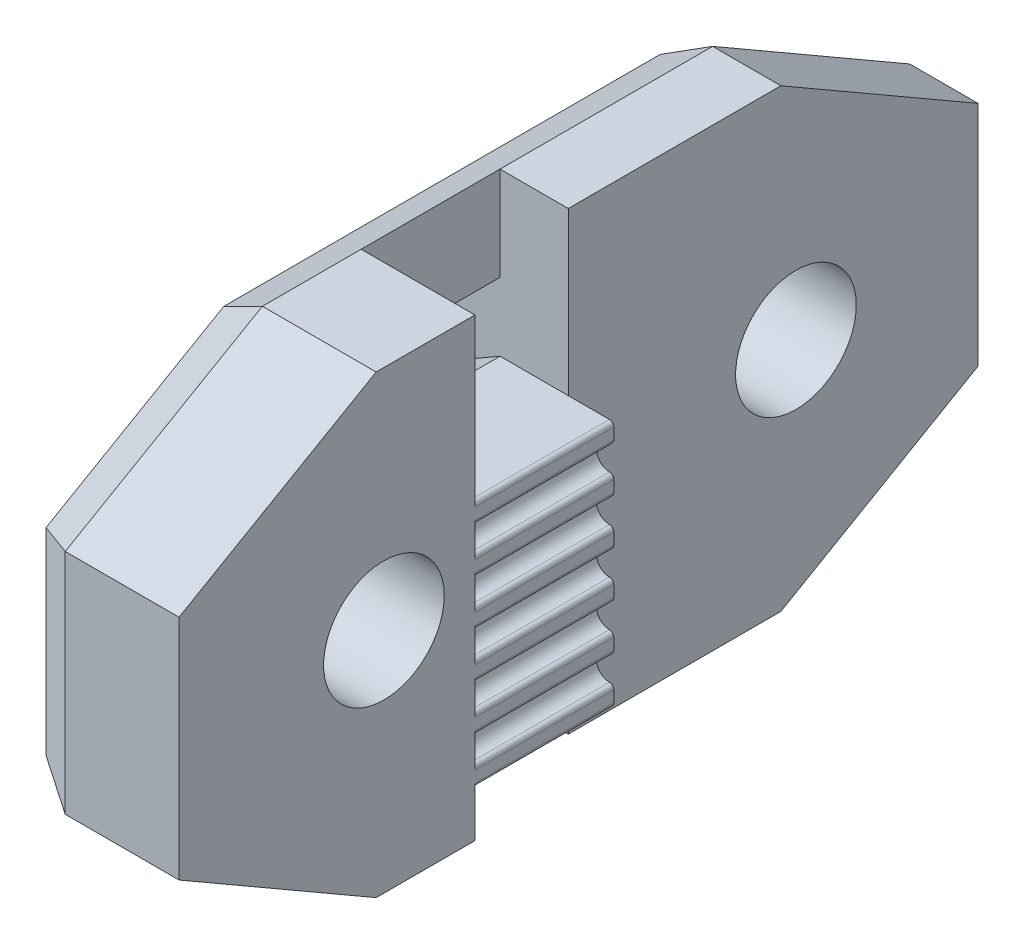
SolidWorks part; units mm, degrees
material "ABS"
ref_plane "Ebene vorne" through (0, 0, 0) normal (0, 0, 1) x (1, 0, 0)
ref_plane "Ebene oben" through (0, 0, 0) normal (0, 1, 0) x (1, 0, 0)
ref_plane "Ebene rechts" through (0, 0, 0) normal (1, 0, 0) x (0, 0, -1)
sketch "Skizze1" plane through (0, 0, 0) normal (0, 0, 1) x (1, 0, 0)
  line L0 (0, 0) -> (0, 9.44)
  line L1 (0, 9.44) -> (-7.24, 9.44) construction
  line L2 (-7.05, 10.19) -> (-7.05, 10.69)
  line L3 (-7.05, 8.69) -> (-7.05, 8.19)
  line L4 (-7.24, 10.88) -> (-9.24, 10.88)
  line L5 (-9.24, 10.88) -> (-9.24, 0)
  line L6 (-7.05, 6.69) -> (-7.05, 6.19)
  line L7 (-7.05, 4.69) -> (-7.05, 4.19)
  line L8 (-7.05, 2.69) -> (-7.05, 2.19)
  line L9 (-7.05, 0.69) -> (-7.05, 0.19)
  line L10 (-7.05, -1.31) -> (-7.05, -1.81) construction
  line L11 (-7.05, -3.31) -> (-7.05, -3.81) construction
  line L12 (-7.05, -5.31) -> (-7.05, -5.81) construction
  line L13 (-7.05, -7.31) -> (-7.05, -7.81) construction
  line L14 (-7.05, -9.31) -> (-7.05, -9.81) construction
  line L15 (-7.24, 0) -> (-9.24, 0)
  line L16 (0, 9.44) -> (0, 10.88)
  line L17 (0, 10.88) -> (-6, 10.88)
  line L18 (-6, 10.88) -> (-6, 0)
  line L19 (-6, 0) -> (0, 0)
  arc A0 (-7.24, 10) -> (-7.24, 8.88) centre (-7.24, 9.44) ccw
  arc A1 (-7.24, 8) -> (-7.24, 6.88) centre (-7.24, 7.44) ccw
  arc A2 (-7.05, 8.69) -> (-7.24, 8.88) centre (-7.24, 8.69) ccw
  arc A3 (-7.24, 8) -> (-7.05, 8.19) centre (-7.24, 8.19) ccw
  arc A4 (-7.05, 10.19) -> (-7.24, 10) centre (-7.24, 10.19) cw
  arc A5 (-7.24, 10.88) -> (-7.05, 10.69) centre (-7.24, 10.69) cw
  arc A6 (-7.24, 8) -> (-7.24, 6.88) centre (-7.24, 7.44) ccw
  arc A7 (-7.05, 6.69) -> (-7.24, 6.88) centre (-7.24, 6.69) ccw
  arc A8 (-7.24, 6) -> (-7.05, 6.19) centre (-7.24, 6.19) ccw
  arc A9 (-7.24, 6) -> (-7.24, 4.88) centre (-7.24, 5.44) ccw
  arc A10 (-7.05, 4.69) -> (-7.24, 4.88) centre (-7.24, 4.69) ccw
  arc A11 (-7.24, 4) -> (-7.05, 4.19) centre (-7.24, 4.19) ccw
  arc A12 (-7.24, 4) -> (-7.24, 2.88) centre (-7.24, 3.44) ccw
  arc A13 (-7.05, 2.69) -> (-7.24, 2.88) centre (-7.24, 2.69) ccw
  arc A14 (-7.24, 2) -> (-7.05, 2.19) centre (-7.24, 2.19) ccw
  arc A15 (-7.24, 2) -> (-7.24, 0.88) centre (-7.24, 1.44) ccw
  arc A16 (-7.05, 0.69) -> (-7.24, 0.88) centre (-7.24, 0.69) ccw
  arc A17 (-7.24, 0) -> (-7.05, 0.19) centre (-7.24, 0.19) ccw
  arc A18 (-7.24, 0) -> (-7.24, -1.12) centre (-7.24, -0.56) ccw construction
  arc A19 (-7.05, -1.31) -> (-7.24, -1.12) centre (-7.24, -1.31) ccw construction
  arc A20 (-7.24, -2) -> (-7.05, -1.81) centre (-7.24, -1.81) ccw construction
  arc A21 (-7.24, -2) -> (-7.24, -3.12) centre (-7.24, -2.56) ccw construction
  arc A22 (-7.05, -3.31) -> (-7.24, -3.12) centre (-7.24, -3.31) ccw construction
  arc A23 (-7.24, -4) -> (-7.05, -3.81) centre (-7.24, -3.81) ccw construction
  arc A24 (-7.24, -4) -> (-7.24, -5.12) centre (-7.24, -4.56) ccw construction
  arc A25 (-7.05, -5.31) -> (-7.24, -5.12) centre (-7.24, -5.31) ccw construction
  arc A26 (-7.24, -6) -> (-7.05, -5.81) centre (-7.24, -5.81) ccw construction
  arc A27 (-7.24, -6) -> (-7.24, -7.12) centre (-7.24, -6.56) ccw construction
  arc A28 (-7.05, -7.31) -> (-7.24, -7.12) centre (-7.24, -7.31) ccw construction
  arc A29 (-7.24, -8) -> (-7.05, -7.81) centre (-7.24, -7.81) ccw construction
  arc A30 (-7.24, -8) -> (-7.24, -9.12) centre (-7.24, -8.56) ccw construction
  arc A31 (-7.05, -9.31) -> (-7.24, -9.12) centre (-7.24, -9.31) ccw construction
  arc A32 (-7.24, -10) -> (-7.05, -9.81) centre (-7.24, -9.81) ccw construction
  point P6 (-7.8, 9.44)
  dimension "D1" = 0.56
  dimension "D3" = 0.75
  dimension "D2" = 2
  dimension "D5" = 2
  dimension "D6" = 1.8
  dimension "D7" = 6
  dimension "D8" = 10.88
  dimension "D4" = 10
extrude "Aufsatz-Linear austragen1" add sketch "Skizze1" along normal blind 6.1
sketch "Skizze2" plane through (0, 0, 6.1) normal (0, 0, 1) x (1, 0, 0)
  line L1 (-6, 10.88) -> (0, 10.88)
  line L2 (-6, 10.88) -> (-6, 0)
  line L3 (-6, 0) -> (0, 0)
  line L4 (0, 10.88) -> (0, 0)
extrude "Schnitt-Linear austragen1" cut sketch "Skizze2" against normal up to surface (6.1 mm away) up to face at (-3, 5.44, 0)
sketch "Skizze3" plane through (-9.24, 0, 0) normal (-1, 0, 0) x (0, 0, 1)
  line L0 (6.1, 0) -> (0, 0) construction
  line L1 (0, -2) -> (-13, -2)
  line L2 (0, -2) -> (0, 18)
  line L3 (0, 18) -> (-13, 18)
  line L4 (-13, -2) -> (-13, 18)
  line L5 (0, 10.88) -> (0, 0) construction
  line L6 (-4, 8) -> (0, 8) construction
  line L7 (6.1, 10.88) -> (6.1, 0) construction
  line L8 (0, 18) -> (6.1, 18)
  line L9 (0, 18) -> (0, 13.88)
  line L10 (0, 13.88) -> (6.1, 13.88)
  line L11 (6.1, 18) -> (6.1, 13.88)
  line L12 (6.1, 10.88) -> (0, 10.88) construction
  circle A0 centre (-4, 8) radius 2.65
  dimension "D4" = 5.3
  dimension "D1" = 20
  dimension "D2" = 2
  dimension "D3" = 4
  dimension "D5" = 13
  dimension "D6" = 3
extrude "Aufsatz-Linear austragen2" add sketch "Skizze3" against normal blind 2.19
sketch "Skizze4" plane through (-9.24, 0, 0) normal (-1, 0, 0) x (0, 0, 1)
  line L1 (6.1, 18) -> (24.1, 18)
  line L2 (6.1, 18) -> (6.1, -2)
  line L3 (6.1, -2) -> (24.1, -2)
  line L4 (24.1, 18) -> (24.1, -2)
  line L10 (6.1, 10.88) -> (0, 10.88)
  line L11 (0, 10.88) -> (0, 13.88)
  line L12 (0, 13.88) -> (6.1, 13.88)
  line L13 (6.1, 13.88) -> (6.1, 18)
  line L14 (6.1, 18) -> (-13, 18)
  line L15 (-13, 18) -> (-13, -2)
  line L16 (-13, -2) -> (0, -2)
  line L17 (0, -2) -> (0, 0)
  line L18 (0, 0) -> (6.1, 0)
  line L19 (6.1, 0) -> (6.1, 10.88)
  line L20 (6.1, 10.88) -> (0, 10.88)
  line L21 (0, 10.88) -> (0, 13.88)
  line L22 (0, 13.88) -> (6.1, 13.88)
  line L23 (6.1, 13.88) -> (6.1, 18)
  line L24 (6.1, 18) -> (-13, 18)
  line L25 (-13, 18) -> (-13, -2)
  line L26 (-13, -2) -> (0, -2)
  line L27 (0, -2) -> (0, 0)
  line L28 (0, 0) -> (6.1, 0)
  line L29 (6.1, 0) -> (6.1, 10.88)
  circle A0 centre (-4, 8) radius 2.65 construction
  circle A1 centre (-4, 8) radius 2.65
  circle A2 centre (16.1, 8) radius 2.65
  line M11 (6.1, 10.88) -> (0, 10.88)
  line M12 (0, 10.88) -> (0, 13.88)
  line M13 (0, 13.88) -> (6.1, 13.88)
  line M14 (6.1, 13.88) -> (6.1, 18)
  line M15 (6.1, 18) -> (-13, 18)
  line M16 (-13, 18) -> (-13, -2)
  line M17 (-13, -2) -> (0, -2)
  line M18 (0, -2) -> (0, 0)
  line M19 (0, 0) -> (6.1, 0)
  line M20 (6.1, 0) -> (6.1, 10.88)
  circle M21 centre (-4, 8) radius 2.65
  dimension "D2" = 10
  dimension "D3" = 8
  dimension "D1" = 0
extrude "Aufsatz-Linear austragen3" add sketch "Skizze4" along normal offset from surface (4.81 mm away) 7 contours L4 L1 L2 L3 A2 M14 M20 | M20 M11 M12 M13 M14 M15 M16 M17 M18 M19 M21 up to face at (-7.05, 6.344, 1.98)
sketch "Skizze5" plane through (-9.24, 0, 0) normal (1, 0, 0) x (0, 0, -1)
  line L7 (-6.1, 13.88) -> (-6.1, 18)
  line L8 (-6.1, 18) -> (-24.1, 18)
  line L9 (-24.1, 18) -> (-24.1, -2)
  line L10 (-24.1, -2) -> (-6.1, -2)
  line L11 (-6.1, -2) -> (-6.1, 0)
  line L12 (-6.1, 0) -> (-6.1, 10.88)
  line L13 (-6.1, 10.88) -> (-6.1, 13.88)
  line L14 (-6.1, 13.88) -> (-6.1, 18)
  line L15 (-6.1, 18) -> (-24.1, 18)
  line L16 (-24.1, 18) -> (-24.1, -2)
  line L17 (-24.1, -2) -> (-6.1, -2)
  line L18 (-6.1, -2) -> (-6.1, 0)
  line L19 (-6.1, 0) -> (-6.1, 10.88)
  line L20 (-6.1, 10.88) -> (-6.1, 13.88)
  circle A0 centre (-16.1, 8) radius 2.65 construction
  circle A1 centre (-16.1, 8) radius 2.65
  dimension "D1" = 0
extrude "Aufsatz-Linear austragen4" add sketch "Skizze5" along normal offset from surface (0.19 mm away) 2 up to face at (-7.05, 6.344, 1.98)
chamfer "Fase1" distance 5 angle 60 4 edges at (-10.55, 18, -13) (-11.55, 18, 24.1) (-11.55, -2, 24.1) (-10.55, -2, -13)
chamfer "Fase2" distance 2 angle 30 11 edges at (-14.05, 10.88, 3.05) (-14.05, 13.88, 3.05) (-14.05, -2, -2.1699) (-14.05, -2, 10.7699) (-14.05, 0.5, 19.7699) (-14.05, 8, 24.1) (-14.05, 15.5, 19.7699) (-14.05, 18, 5.55) (-14.05, 15.5, -8.6699) (-14.05, 8, -13) (-14.05, 0.5, -8.6699)
sketch "Skizze11" plane through (0, -2, 0) normal (0, -1, 0) x (1, 0, 0)
  line L0 (-14.05, 7.6) -> (-14.05, 6.1)
  line L1 (-14.05, 6.1) -> (-14.05, 15.1303) construction
  line L2 (-14.05, 0) -> (-14.05, -1.5)
  line L3 (-12.55, 1.5) -> (-12.55, 4.6)
  line L4 (-11.05, 1.5) -> (-11.05, 4.6)
  arc A0 (-14.05, 6.1) -> (-12.55, 4.6) centre (-14.05, 4.6) cw
  arc A1 (-14.05, 0) -> (-12.55, 1.5) centre (-14.05, 1.5) ccw
  arc A2 (-14.05, -1.5) -> (-11.05, 1.5) centre (-14.05, 1.5) ccw
  arc A3 (-14.05, 7.6) -> (-11.05, 4.6) centre (-14.05, 4.6) cw
  dimension "D1" = 1.5
  dimension "D2" = 1.5
extrude "Schnitt-Linear austragen3" cut sketch "Skizze11" against normal blind 2.5 from offset 4
mirror "Spiegeln1" about plane through (-63.1975, -24.9245, 24.1) normal (0, 0, 1) of bodies 113
delete or keep bodies "Körper-Löschen1" type delete bodies bodies 113
sketch "Skizze12" plane through (0, 18, 0) normal (0, 1, 0) x (1, 0, 0)
  line L0 (-7.24, -48.2) -> (-12.05, -48.2) construction
  line L1 (-7.05, -42.1) -> (-12.05, -42.1)
  line L2 (-7.05, -42.1) -> (-7.05, -48.2)
  line L3 (-7.05, -48.2) -> (-12.05, -48.2)
  line L4 (-12.05, -42.1) -> (-12.05, -48.2)
  line L5 (-14.05, -33.0697) -> (-14.05, -52.2303) construction
  dimension "D1" = 2
  dimension "D2" = 5
extrude "Schnitt-Linear austragen4" cut sketch "Skizze12" against normal up to surface (4.12 mm away)
